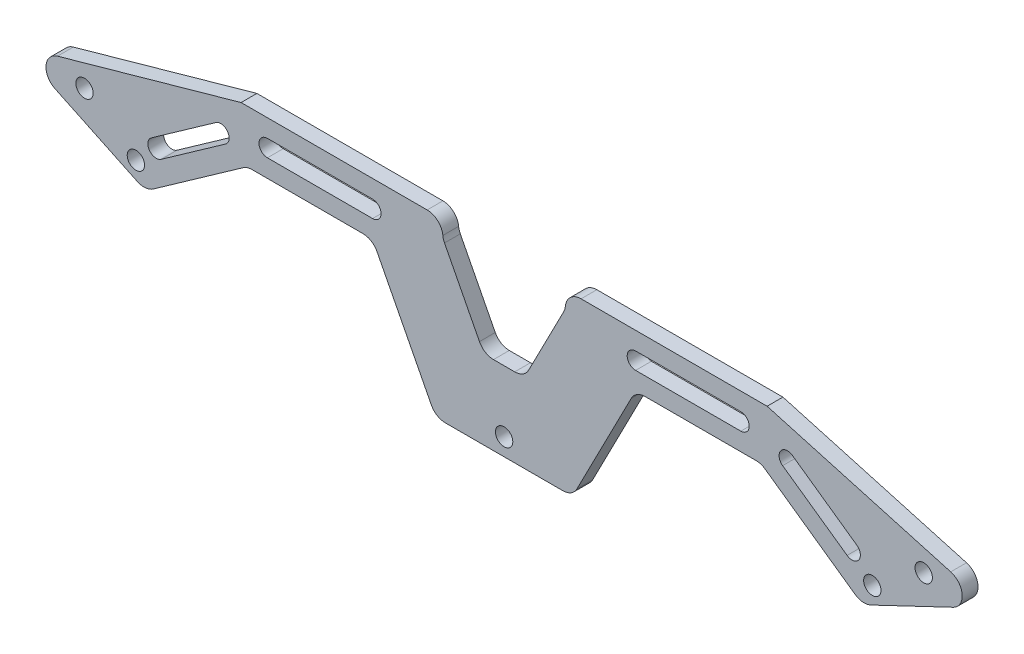
SolidWorks part; units mm, degrees
material "Thornel Mat VMA"
ref_plane "前视基准面" through (0, 0, 0) normal (0, 0, 1) x (1, 0, 0)
ref_plane "上视基准面" through (0, 0, 0) normal (0, 1, 0) x (1, 0, 0)
ref_plane "右视基准面" through (0, 0, 0) normal (1, 0, 0) x (0, 0, -1)
sketch "草图1" plane through (0, 0, 0) normal (0, 0, 1) x (1, 0, 0)
  line L0 (-79.7686, -13.0304) -> (-70, -20) construction
  line L1 (0, -31.5972) -> (0, 33.9839) construction
  line L3 (-92.5924, -12.4801) -> (-72.2412, -27)
  line L4 (-92.5924, -12.4801) -> (-50, -0.5)
  line L5 (-72.2412, -27) -> (-48.8516, -10.5)
  line L6 (-48.8516, -10.5) -> (0, -10.5)
  line L7 (-50, -0.5) -> (0, -0.5)
  line L8 (0, -0.5) -> (0, -10.5)
  circle A0 centre (-79.7686, -13.0304) radius 1.65
  circle A1 centre (-70, -20) radius 1.65
  dimension "D3" = 3.3
  dimension "D4" = 3.3
  dimension "D5" = 20
  dimension "D1" = 12
  dimension "D2" = 70
  dimension "D6" = 54.493
  dimension "D7" = 7
  dimension "D8" = 25
  dimension "D9" = 26.5
  dimension "D11" = 10
  dimension "D12" = 27
  dimension "D13" = 50
extrude "凸台-拉伸1" add sketch "草图1" along normal blind 3
mirror "镜向1" about plane through (0, -0.5, 3) normal (-1, 0, 0) of bodies 106
sketch "草图2" plane through (0, 0, 3) normal (0, 0, 1) x (1, 0, 0)
  line L0 (-92.5924, -12.4801) -> (-68.1555, -24.1178)
  line L1 (-72.2412, -27) -> (-48.8516, -10.5) construction
  line L2 (-68.1555, -24.1178) -> (-72.2412, -27)
  line L3 (-72.2412, -27) -> (-92.5924, -12.4801)
  line L4 (92.5924, -12.4801) -> (68.1555, -24.1178)
  line L5 (72.2412, -27) -> (48.8516, -10.5) construction
  line L6 (68.1555, -24.1178) -> (72.2412, -27)
  line L7 (72.2412, -27) -> (92.5924, -12.4801)
  dimension "D1" = 5
extrude "切除-拉伸1" cut sketch "草图2" against normal blind 3
sketch "草图3" plane through (0, 0, 3) normal (0, 0, 1) x (1, 0, 0)
  line L0 (-25, -10.5) -> (-13, -33.83)
  line L1 (-48.8516, -10.5) -> (48.8516, -10.5) construction
  line L2 (-13, -33.83) -> (13, -33.83)
  line L3 (13, -33.83) -> (25, -10.5)
  line L4 (25, -10.5) -> (-25, -10.5)
  line L5 (0, 0.9445) -> (0, -43.1519) construction
  dimension "D1" = 13
  dimension "D2" = 13
  dimension "D3" = 25
  dimension "D4" = 25
  dimension "D5" = 23.33
extrude "凸台-拉伸2" add sketch "草图3" against normal up to surface (3 mm away) up to face at (0, -11.8995, 0)
sketch "草图4" plane through (0, 0, 3) normal (0, 0, 1) x (1, 0, 0)
  line L6 (-11.6611, -3.639) -> (-11.6611, -0.5)
  line L7 (50, -0.5) -> (-50, -0.5) construction
  line L8 (-11.6611, -0.5) -> (11.6611, -0.5)
  line L9 (3.8475, -18.83) -> (11.6611, -3.639)
  line L10 (-3.8475, -18.83) -> (3.8475, -18.83)
  line L11 (-11.6611, -3.639) -> (-3.8475, -18.83)
  line L12 (3.8475, -18.83) -> (11.6611, -3.639)
  line L13 (-3.8475, -18.83) -> (3.8475, -18.83)
  line L14 (-11.6611, -3.639) -> (-3.8475, -18.83)
  line L15 (11.6611, -0.5) -> (11.6611, -3.639)
  dimension "D1" = 15
extrude "切除-拉伸2" cut sketch "草图4" against normal blind 3
fillet "圆角1" radius 3 14 edges at (-48.8516, -10.5, 1.5) (-92.5924, -12.4801, 1.5) (92.5924, -12.4801, 1.5) (48.8516, -10.5, 1.5) (-68.1555, -24.1178, 1.5) (68.1555, -24.1178, 1.5) (-13, -33.83, 1.5) (13, -33.83, 1.5) (25, -10.5, 1.5) (-25, -10.5, 1.5) (11.6611, -3.639, 1.5) (3.8475, -18.83, 1.5) (-3.8475, -18.83, 1.5) (-11.6611, -3.639, 1.5)
fillet "圆角2" radius 3 2 edges at (11.6611, -0.5, 1.5) (-11.6611, -0.5, 1.5)
sketch "草图7" plane through (0, 0, 3) normal (0, 0, 1) x (1, 0, 0)
  line L0 (-11.1695, -33.83) -> (11.1695, -33.83) construction
  circle A0 centre (0, -30.53) radius 1.65
  dimension "D1" = 3.3
  dimension "D2" = 3.3
extrude "切除-拉伸4" cut sketch "草图7" against normal blind 10
sketch "草图5" plane through (0, 0, 3) normal (0, 0, 1) x (1, 0, 0)
  line L0 (-45, -5.5) -> (-25, -5.5) construction
  line L1 (-45, -3.9) -> (-25, -3.9)
  line L2 (-45, -7.1) -> (-25, -7.1)
  line L3 (-66.1285, -16.1467) -> (-53.8715, -7.5) construction
  line L4 (-67.0508, -14.8392) -> (-54.7938, -6.1926)
  line L5 (-65.2062, -17.4541) -> (-52.9492, -8.8074)
  line L7 (-66.7211, -23.1059) -> (-49.6292, -11.0486) construction
  line L8 (0, -18.83) -> (0, 29.0259) construction
  line L9 (-2.0169, -18.83) -> (2.0169, -18.83) construction
  arc A0 (-45, -3.9) -> (-45, -7.1) centre (-45, -5.5) ccw
  arc A1 (-25, -7.1) -> (-25, -3.9) centre (-25, -5.5) ccw
  arc A2 (-67.0508, -14.8392) -> (-65.2062, -17.4541) centre (-66.1285, -16.1467) ccw
  arc A3 (-52.9492, -8.8074) -> (-54.7938, -6.1926) centre (-53.8715, -7.5) ccw
  point P2 (-35, -5.5)
  point P7 (-60, -11.8233)
  dimension "D3" = 1.6
  dimension "D5" = 1.6
  dimension "D1" = 20
  dimension "D2" = 35
  dimension "D4" = 5.5
  dimension "D6" = 60
  dimension "D7" = 15
  dimension "D8" = 7.5
extrude "切除-拉伸3" cut sketch "草图5" against normal blind 3
mirror "镜向2" about plane through (0, 0, 0) normal (1, 0, 0) of "切除-拉伸3"
